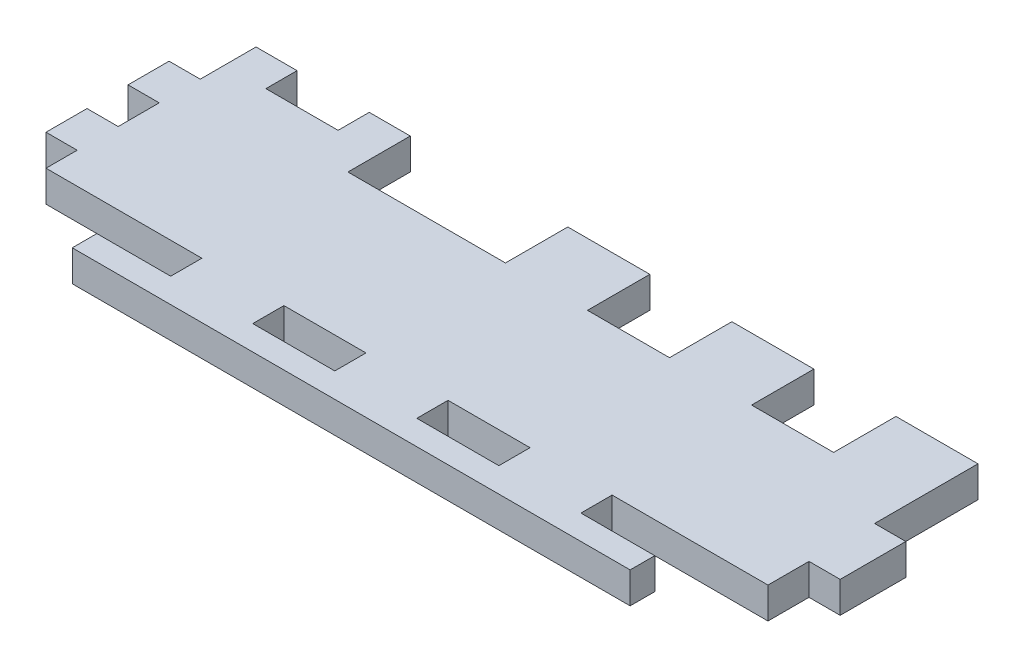
SolidWorks part; units mm, degrees
material "Maple"
ref_plane "Front Plane" through (0, 0, 0) normal (0, 0, 1) x (1, 0, 0)
ref_plane "Top Plane" through (0, 0, 0) normal (0, 1, 0) x (1, 0, 0)
ref_plane "Right Plane" through (0, 0, 0) normal (1, 0, 0) x (0, 0, -1)
sketch "Sketch1" plane through (0, 0, 0) normal (0, 1, 0) x (1, 0, 0)
  line L1 (0, 0) -> (88, 0)
  line L2 (0, 0) -> (0, -18)
  line L3 (0, -18) -> (88, -18)
  line L4 (88, 0) -> (88, -18)
  dimension "D1" = 88
  dimension "D2" = 18
extrude "Boss-Extrude1" add sketch "Sketch1" along normal blind 3.8
sketch "Sketch2" plane through (0, 0, 0) normal (0, -1, 0) x (1, 0, 0)
  line L0 (88, 0) -> (0, 0) construction
  line L1 (0, 0) -> (18.8, 0)
  line L2 (0, 0) -> (0, -3.8)
  line L3 (0, -3.8) -> (18.8, -3.8)
  line L4 (18.8, 0) -> (18.8, -3.8)
  line L5 (0, 0) -> (0, 18) construction
  line L6 (88, 18) -> (88, 0) construction
  dimension "D1" = 69.2
  dimension "D2" = 3.8
extrude "Boss-Extrude2" add sketch "Sketch2" against normal through all
sketch "Sketch3" plane through (0, 0, 0) normal (0, -1, 0) x (1, 0, 0)
  line L0 (44, 18) -> (44, 0) construction
  line L1 (0, 18) -> (88, 18) construction
  line L2 (88, 0) -> (18.8, 0) construction
  line L4 (39, 21.8) -> (49, 21.8)
  line L5 (39, 21.8) -> (39, 18)
  line L6 (39, 18) -> (49, 18)
  line L7 (49, 21.8) -> (49, 18)
  line L8 (39, 21.8) -> (49, 18) construction
  line L9 (39, 18) -> (49, 21.8) construction
  point P6 (44, 19.9)
  dimension "D1" = 3.8
  dimension "D2" = 10
extrude "Boss-Extrude3" add sketch "Sketch3" against normal through all
pattern_linear "LPattern1" count 3 spacing 20 along (1, 0, 0) count 3 spacing 20 along (-1, 0, 0) of "Boss-Extrude3"
sketch "Sketch4" plane through (0, 0, 0) normal (0, -1, 0) x (-1, 0, 0)
  line L1 (1, -21.8) -> (0, -21.8)
  line L2 (1, -21.8) -> (1, -18)
  line L3 (1, -18) -> (0, -18)
  line L4 (0, -21.8) -> (0, -18)
  line L5 (-89, -21.8) -> (-88, -21.8)
  line L6 (-89, -21.8) -> (-89, -18)
  line L7 (-89, -18) -> (-88, -18)
  line L8 (-88, -21.8) -> (-88, -18)
extrude "Cut-Extrude1" cut sketch "Sketch4" against normal through all
sketch "Sketch5" plane through (0, 0, 0) normal (0, -1, 0) x (-1, 0, 0)
  line L0 (-88, -21.8) -> (-88, 0) construction
  line L1 (0, -21.8) -> (-88, -21.8)
  line L2 (0, -21.8) -> (0, -24.8)
  line L3 (0, -24.8) -> (-88, -24.8)
  line L4 (-88, -21.8) -> (-88, -24.8)
  dimension "D1" = 3
extrude "Boss-Extrude4" add sketch "Sketch5" against normal through all
sketch "Sketch6" plane through (0, 0, 0) normal (0, -1, 0) x (-1, 0, 0)
  line L0 (0, 3.8) -> (-18.8, 3.8) construction
  line L1 (0, 3.8) -> (-5, 3.8)
  line L2 (0, 3.8) -> (0, 7.6)
  line L3 (0, 7.6) -> (-5, 7.6)
  line L4 (-5, 3.8) -> (-5, 7.6)
  line L5 (-18.8, 3.8) -> (-13.8, 3.8)
  line L6 (-18.8, 3.8) -> (-18.8, 7.6)
  line L7 (-18.8, 7.6) -> (-13.8, 7.6)
  line L8 (-13.8, 3.8) -> (-13.8, 7.6)
  dimension "D1" = 3.8
  dimension "D2" = 5
extrude "Boss-Extrude5" add sketch "Sketch6" against normal through all
sketch "Sketch7" plane through (0, 0, 0) normal (0, -1, 0) x (-1, 0, 0)
  line L0 (-88, 0) -> (-18.8, 0) construction
  line L1 (-88, 0) -> (-78, 0)
  line L2 (-88, 0) -> (-88, 7.6)
  line L3 (-88, 7.6) -> (-78, 7.6)
  line L4 (-78, 0) -> (-78, 7.6)
  dimension "D1" = 7.6
  dimension "D2" = 10
extrude "Boss-Extrude6" add sketch "Sketch7" against normal through all
pattern_linear "LPattern2" count 3 spacing 20 along (-1, 0, 0) of "Boss-Extrude6"
sketch "Sketch9" plane through (0, 0, 0) normal (0, -1, 0) x (-1, 0, 0)
  line L0 (0, 7.6) -> (0, -24.8) construction
  line L1 (-9, -21.8) -> (0, -21.8)
  line L2 (-9, -21.8) -> (-9, -18)
  line L3 (-9, -18) -> (0, -18)
  line L4 (0, -21.8) -> (0, -18)
  line L5 (-88, -24.8) -> (-88, 7.6) construction
  line L6 (-79, -21.8) -> (-88, -21.8)
  line L7 (-79, -21.8) -> (-79, -18)
  line L8 (-79, -18) -> (-88, -18)
  line L9 (-88, -21.8) -> (-88, -18)
  line L10 (-69, -18) -> (-79, -18) construction
  line L11 (-9, -18) -> (-19, -18) construction
extrude "Cut-Extrude2" cut sketch "Sketch9" against normal through all
sketch "Sketch10" plane through (0, 0, 0) normal (0, -1, 0) x (-1, 0, 0)
  line L0 (0, 7.6) -> (0, -18) construction
  line L1 (0, -14.2) -> (3.8, -14.2)
  line L2 (0, -14.2) -> (0, -9.2)
  line L3 (0, -9.2) -> (3.8, -9.2)
  line L4 (3.8, -14.2) -> (3.8, -9.2)
  line L10 (0, -18) -> (-19, -18) construction
  line L11 (-88, -18) -> (-88, 7.6) construction
  line L12 (-88, -13) -> (-91.8, -13)
  line L13 (-88, -13) -> (-88, -5)
  line L14 (-88, -5) -> (-91.8, -5)
  line L15 (-91.8, -13) -> (-91.8, -5)
  line L16 (-69, -18) -> (-88, -18) construction
  line L17 (-78, 0) -> (-68, 0) construction
  line L19 (0, -4.2) -> (3.8, -4.2)
  line L20 (0, -4.2) -> (0, 0.8)
  line L21 (0, 0.8) -> (3.8, 0.8)
  line L22 (3.8, -4.2) -> (3.8, 0.8)
  dimension "D1" = 3.8
  dimension "D2" = 3.8
  dimension "D3" = 5
  dimension "D4" = 3.8
  dimension "D5" = 5
  dimension "D6" = 5
  dimension "D7" = 5
extrude "Boss-Extrude8" add sketch "Sketch10" against normal through all
sketch "Sketch11" plane through (0, 0, 0) normal (0, -1, 0) x (-1, 0, 0)
  line L0 (0, -21.8) -> (-19, -21.8) construction
  line L1 (0, -24.8) -> (-10, -24.8)
  line L2 (0, -24.8) -> (0, -21.8)
  line L3 (0, -21.8) -> (-10, -21.8)
  line L4 (-10, -24.8) -> (-10, -21.8)
  line L5 (-69, -21.8) -> (-88, -21.8) construction
  line L6 (-88, -24.8) -> (-78, -24.8)
  line L7 (-88, -24.8) -> (-88, -21.8)
  line L8 (-88, -21.8) -> (-78, -21.8)
  line L9 (-78, -24.8) -> (-78, -21.8)
  dimension "D1" = 10
  dimension "D2" = 10
extrude "Cut-Extrude3" cut sketch "Sketch11" against normal through all
equation "\"D2@Sketch11\"=\"D1@Sketch11\""
